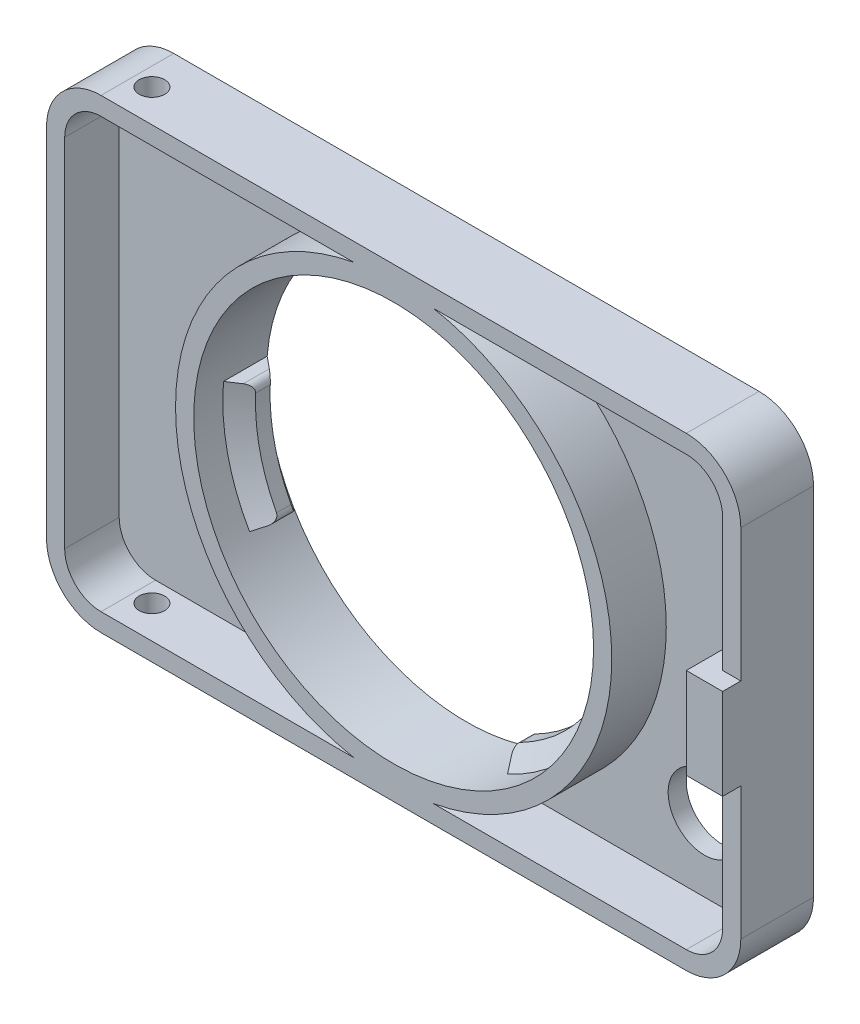
SolidWorks part; units mm, degrees
ref_plane "Front Plane" through (0, 0, 0) normal (0, 0, 1) x (1, 0, 0)
ref_plane "Top Plane" through (0, 0, 0) normal (0, 1, 0) x (1, 0, 0)
ref_plane "Right Plane" through (0, 0, 0) normal (1, 0, 0) x (0, 0, -1)
sketch "Sketch1" plane through (0, 0, 0) normal (0, 0, 1) x (1, 0, 0)
  line L1 (-80.5, 64) -> (80.5, 64)
  line L2 (-95.5, 49) -> (-95.5, -49)
  line L3 (-80.5, -64) -> (80.5, -64)
  line L4 (95.5, 49) -> (95.5, -49)
  line L5 (-95.5, 64) -> (95.5, -64) construction
  line L6 (-95.5, -64) -> (95.5, 64) construction
  arc A0 (-95.5, -49) -> (-80.5, -64) centre (-80.5, -49) ccw
  arc A1 (80.5, -64) -> (95.5, -49) centre (80.5, -49) ccw
  arc A2 (80.5, 64) -> (95.5, 49) centre (80.5, 49) cw
  arc A3 (-80.5, 64) -> (-95.5, 49) centre (-80.5, 49) ccw
  point P0 (0, 0)
  dimension "D3" = 15
  dimension "D1" = 128
  dimension "D2" = 191
extrude "Boss-Extrude1" add sketch "Sketch1" along normal blind 20
sketch "Sketch2" plane through (0, 0, 20) normal (0, 0, 1) x (1, 0, 0)
  circle A0 centre (0, 0) radius 55
  dimension "D1" = 110
extrude "Cut-Extrude1" cut sketch "Sketch2" against normal through all
shell "Shell1" thickness 5
sketch "Sketch3" plane through (0, 0, 0) normal (1, 0, 0) x (0, 0, -1)
  line L0 (0, 55) -> (-12, 55)
  line L1 (0, 49) -> (0, 64) construction
  line L2 (0, -55) -> (0, 55) construction
  line L3 (-12, 55) -> (-8, 50)
  line L4 (-8, 50) -> (-4, 50)
  line L5 (-4, 50) -> (0, 55)
  line L6 (-6, 50) -> (-6, 55) construction
  line L7 (-20, 64) -> (0, 64) construction
  point P10 (0, 54.6554)
  dimension "D1" = 9
  dimension "D2" = 5
  dimension "D3" = 12
  dimension "D4" = 4
sketch "Sketch4" plane through (0, 0, 0) normal (0, 0, 1) x (1, 0, 0)
  line L0 (0, 50) -> (0, 55) construction
  arc A0 (0, 50) -> (28.6182, 41) centre (0, 0) cw
  dimension "D1" = 30
sweep "Sweep1" add profiles "Sketch3" path "Sketch4"
fillet "Fillet1" radius 2 2 edges at (0, 50, 6) (28.6182, 41, 6)
pattern_circular "CirPattern1" count 3 over 360 about axis through (0, 0, 0) along (0, 0, 1) of "Fillet1", "Sweep1"
sketch "Sketch5" plane through (0, 0, 0) normal (0, 0, -1) x (-1, 0, 0)
  line L0 (80.5, -64) -> (-80.5, -64) construction
  line L1 (-95.5, -49) -> (-95.5, 49) construction
  circle A0 centre (-70.5, -39) radius 10
  dimension "D1" = 20
  dimension "D2" = 25
  dimension "D3" = 25
extrude "Cut-Extrude2" cut sketch "Sketch5" against normal through all
sketch "Sketch6" plane through (0, 0, 0) normal (0, 1, 0) x (1, 0, 0)
  line L0 (80.5, -20) -> (-80.5, -20) construction
  line L1 (-95.5, -20) -> (-95.5, 0) construction
  circle A0 centre (-75.5, -11) radius 3.5
  dimension "D1" = 7
  dimension "D2" = 9
  dimension "D3" = 20
extrude "Cut-Extrude3" cut sketch "Sketch6" against normal through all both and the other way through all
sketch "Sketch7" plane through (0, 0, 5) normal (0, 0, 1) x (1, 0, 0)
  line L1 (95.5, 12.5) -> (85.5, 12.5)
  line L2 (95.5, 12.5) -> (95.5, -12.5)
  line L3 (95.5, -12.5) -> (85.5, -12.5)
  line L4 (85.5, 12.5) -> (85.5, -12.5)
  line L5 (95.5, 12.5) -> (85.5, -12.5) construction
  line L6 (95.5, -12.5) -> (85.5, 12.5) construction
  line L7 (0, 0) -> (90.5, 0) construction
  line L8 (95.5, -49) -> (95.5, 49) construction
  point P0 (90.5, 0)
  point P5 (89.0562, -12.5)
  point P10 (95.5, -12.5)
  dimension "D1" = 25
  dimension "D2" = 10
extrude "Boss-Extrude2" add sketch "Sketch7" along normal blind 20
